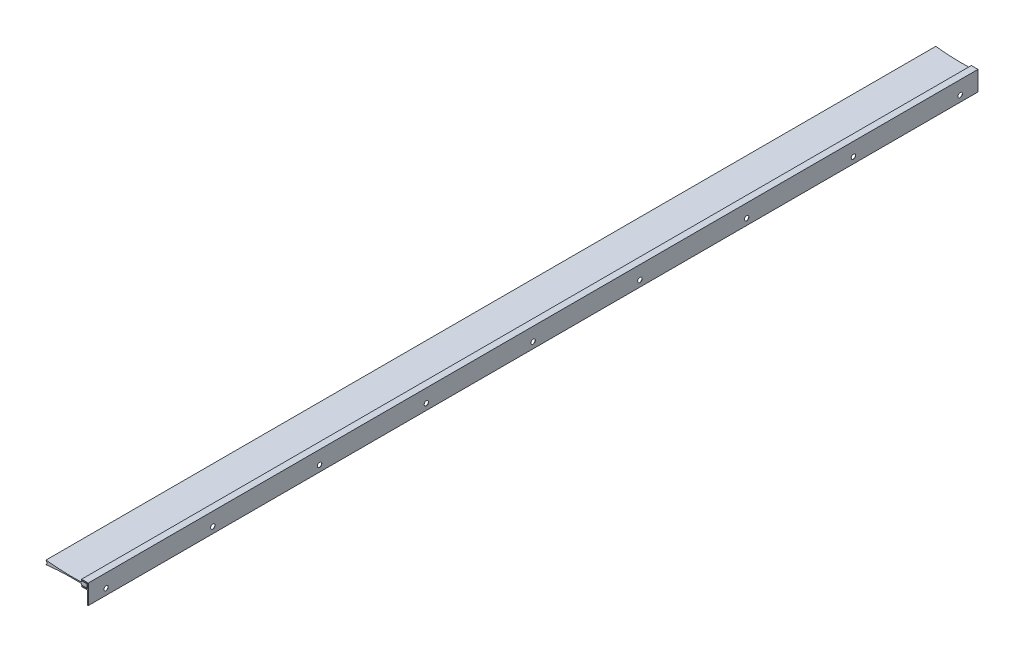
SolidWorks part; units mm, degrees
ref_plane "Front Plane" through (0, 0, 0) normal (0, 0, 1) x (1, 0, 0)
ref_plane "Top Plane" through (0, 0, 0) normal (0, 1, 0) x (1, 0, 0)
ref_plane "Right Plane" through (0, 0, 0) normal (1, 0, 0) x (0, 0, -1)
sketch "Sketch1" plane through (0, 0, 0) normal (0, 0, 1) x (1, 0, 0)
  line L0 (0, 7.2) -> (7.5, 7.2)
  line L5 (0, 0) -> (0, 1)
  line L6 (0, 1) -> (6.5, 1)
  line L7 (6.5, 1) -> (6.5, 6.2)
  line L8 (6.5, 6.2) -> (0, 6.2)
  line L9 (0, 6.2) -> (0, 7.2)
  line L10 (7.5, 7.2) -> (7.5, -14.8)
  line L11 (7.5, -14.8) -> (6.5, -14.8)
  line L12 (6.5, -14.8) -> (6.5, 0)
  line L13 (6.5, 0) -> (0, 0)
  dimension "D1" = 7.5
  dimension "D2" = 7.2
  dimension "D3" = 22
  dimension "D4" = 1
extrude "Boss-Extrude1" add sketch "Sketch1" along normal mid plane 1000
sketch "Sketch2" plane through (0, 0, 500) normal (0, 0, 1) x (1, 0, 0)
  line L0 (6, 3.6) -> (-38.5, 3.6) construction
  line L1 (0, 5.7) -> (6, 5.7)
  line L2 (0, 5.7) -> (0, 4.3)
  line L3 (0, 1.5) -> (6, 1.5)
  line L4 (6, 5.7) -> (6, 1.5)
  line L5 (-40, 5.8419) -> (-38.5, 3.6)
  line L6 (-38.5, 3.6) -> (-40, 1.3581)
  line L7 (0, 2.9) -> (0, 1.5)
  line L8 (6.5, 6.2) -> (6.5, 1) construction
  line L9 (0, 1.5) -> (0, 1.2) construction
  line L10 (0, 1) -> (0, 0) construction
  line L11 (6.5, 1) -> (0, 1) construction
  line L12 (6, 3.6) -> (6.5, 3.6) construction
  line L13 (-40, 5.8419) -> (-40, 1.3581) construction
  line L14 (-38.5, 3.6) -> (-40, 3.6) construction
  line L15 (-20.0297, 4.3) -> (-20.0297, 2.9) construction
  line L16 (-20.0297, 4.3) -> (0, 4.3) construction
  line L17 (0, 4.3) -> (0, 2.9) construction
  arc A0 (0, 4.3) -> (-40, 5.8419) centre (-10.0149, 264.107) cw
  arc A1 (0, 2.9) -> (-40, 1.3581) centre (-10.0149, -256.907) ccw
  dimension "D4" = 260
  dimension "D1" = 0.5
  dimension "D2" = 0.5
  dimension "D3" = 40
  dimension "D5" = 1.5
extrude "Boss-Extrude2" add sketch "Sketch2" against normal up to surface (1000 mm away) separate body up to face at (4.1, -0.08, -500)
hole_wizard "CSK for M3 Hex Socket Countersunk Head Screw1" positions "Sketch3" profile "Sketch4" countersink size "M3" standard "DIN"
sketch "Sketch3" plane through (6.5, -6.5, 0) normal (1, 0, 0) x (0, -1, 0)
  line L1 (-6.5, 0) -> (1.3, 0) construction
  line L2 (-13.7, -500) -> (-13.7, 500) construction
  point P0 (1.3, 0)
  dimension "D1" = 15
sketch "Sketch4" plane through (6.5, -7.8, 0) normal (0, 1, 0) x (0, 0, 1)
  line L0 (0, 0) -> (0, 11.0215)
  line L1 (0, 11.0215) -> (1.7, 10)
  line L2 (1.7, 10) -> (1.7, 1.77)
  line L3 (1.7, 1.77) -> (3.47, 0)
  line L5 (3.47, 0) -> (0, 0)
  line L6 (-1.7, 1.77) -> (-3.47, 0) construction
  line L10 (0, 11.0215) -> (-1.7, 10) construction
  line L11 (0, -6.35) -> (0, 107.95) construction
  dimension "Hole Dia." = 3.4
  dimension "Hole Depth" = 10
  dimension "Near C'Sink Dia." = 6.94
  dimension "Near C'Sink Angle" = 90
  dimension "Drill Angle" = 118
pattern_linear "LPattern1" count 8 spacing 120 along (0, 0, -1) count 8 spacing 120 along (0, 0, 1) of "CSK for M3 Hex Socket Countersunk Head Screw1"
